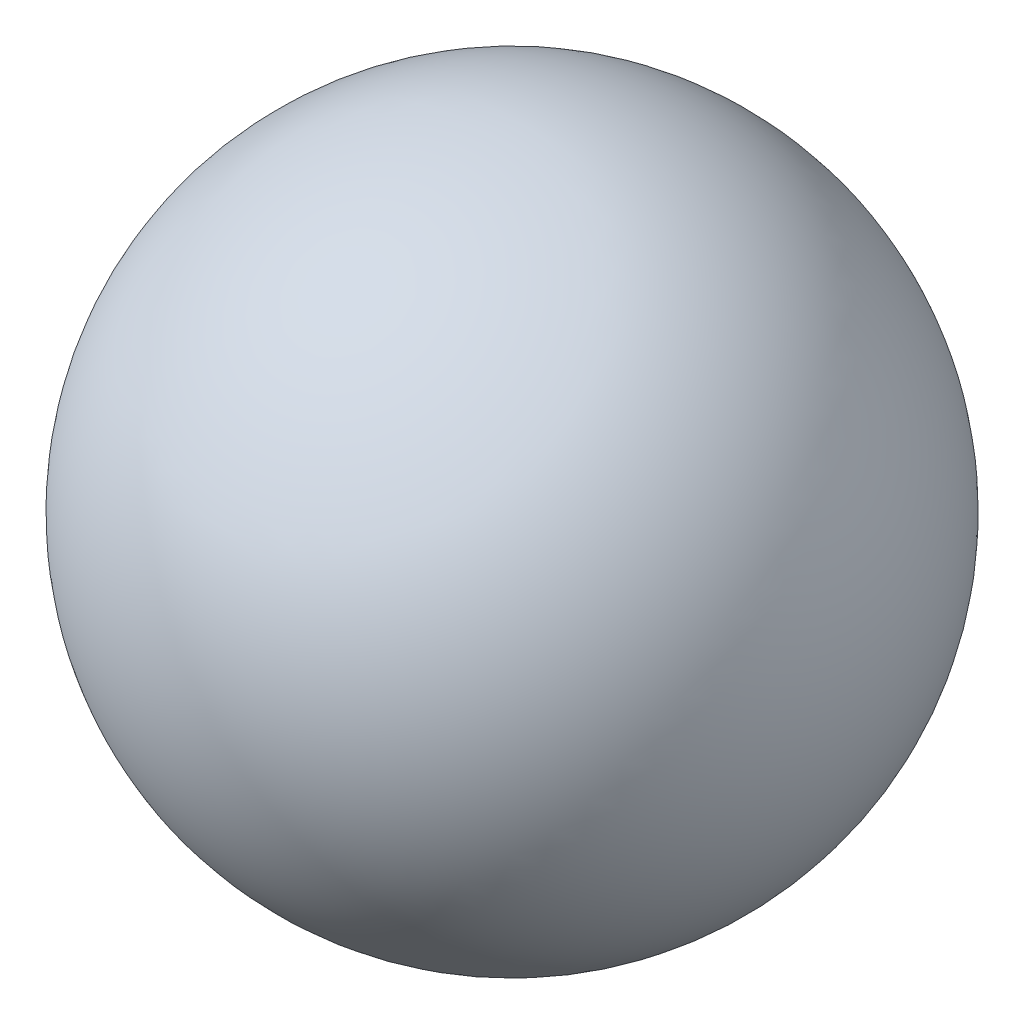
SolidWorks part; units mm, degrees
ref_plane "Front Plane" through (0, 0, 0) normal (0, 0, 1) x (1, 0, 0)
ref_plane "Top Plane" through (0, 0, 0) normal (0, 1, 0) x (1, 0, 0)
ref_plane "Right Plane" through (0, 0, 0) normal (1, 0, 0) x (0, 0, -1)
sketch "Sketch1" plane through (0, 0, 0) normal (0, 1, 0) x (1, 0, 0)
  line L0 (0, 0) -> (0, 254)
  arc A0 (0, 254) -> (0, 0) centre (0, 127) cw
  dimension "D1" = 254
revolve "Revolve1" add sketch "Sketch1" angle 360 about L0
